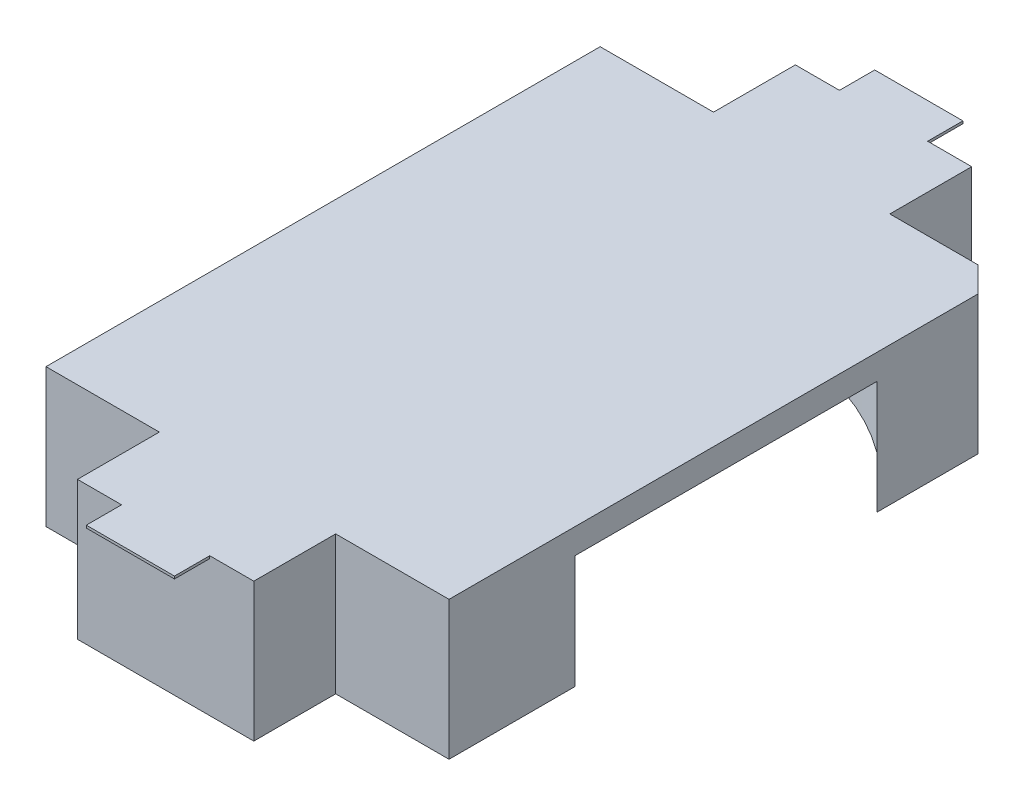
SolidWorks part; units mm, degrees
ref_plane "Front" through (0, 0, 0) normal (0, 0, 1) x (1, 0, 0)
ref_plane "Top" through (0, 0, 0) normal (0, 1, 0) x (1, 0, 0)
ref_plane "Right" through (0, 0, 0) normal (1, 0, 0) x (0, 0, -1)
sketch "Sketch1" plane through (0, 0, 0) normal (0, 1, 0) x (1, 0, 0)
  line L0 (7, 11) -> (8, 10)
  line L1 (-8, -11) -> (8, -11)
  line L2 (-8, -11) -> (-8, 11)
  line L3 (-8, 11) -> (7, 11)
  line L4 (8, -11) -> (8, 10)
  line L5 (-8, -11) -> (8, 11) construction
  line L6 (-8, 11) -> (8, -11) construction
  point P0 (0, 0)
  dimension "D1" = 16
  dimension "D2" = 22
extrude "Boss-Extrude1" add sketch "Sketch1" along normal blind 1
sketch "Sketch2" plane through (0, 0, 0) normal (0, -1, 0) x (1, 0, 0)
  line L0 (-8, -11) -> (-8, -6)
  line L1 (-8, 11) -> (8, 11)
  line L2 (8, 11) -> (8, 6)
  line L3 (8, -10) -> (7, -11)
  line L4 (7, -11) -> (-8, -11)
  line L5 (-8, 6) -> (-8, 11)
  line L6 (8, -6) -> (8, -10)
  arc A0 (-8, -6) -> (8, -6) centre (0, 0) ccw
  arc A1 (8, 6) -> (-8, 6) centre (0, 0) ccw
  dimension "D1" = 20
extrude "Boss-Extrude2" add sketch "Sketch2" along normal blind 4.5
sketch "Sketch3" plane through (0, 1, 0) normal (0, 1, 0) x (1, 0, 0)
  line L0 (-3.5, -11) -> (3.5, -11)
  line L1 (3.5, 14.25) -> (-3.5, 14.25)
  line L2 (3.5, 14.25) -> (3.5, 11)
  line L3 (3.5, -14.25) -> (-3.5, -14.25)
  line L4 (-3.5, 14.25) -> (-3.5, 11)
  line L5 (3.5, 14.25) -> (-3.5, -14.25) construction
  line L6 (3.5, -14.25) -> (-3.5, 14.25) construction
  line L7 (-8, -11) -> (8, -11) construction
  line L8 (-3.5, 11) -> (3.5, 11)
  line L9 (7, 11) -> (-8, 11) construction
  line L10 (3.5, -11) -> (3.5, -14.25)
  line L11 (-3.5, -11) -> (-3.5, -14.25)
  point P0 (0, 0)
  dimension "D1" = 7
  dimension "D2" = 28.5
extrude "Boss-Extrude3" add sketch "Sketch3" against normal up to surface (5.5 mm away) up to face at (0, -4.5, 9.5)
sketch "Sketch4" plane through (0, 1, 0) normal (0, 1, 0) x (1, 0, 0)
  line L1 (1.75, -15.65) -> (-1.75, -15.65)
  line L2 (1.75, -15.65) -> (1.75, 15.65)
  line L3 (1.75, 15.65) -> (-1.75, 15.65)
  line L4 (-1.75, -15.65) -> (-1.75, 15.65)
  line L5 (1.75, -15.65) -> (-1.75, 15.65) construction
  line L6 (1.75, 15.65) -> (-1.75, -15.65) construction
  point P0 (0, 0)
  dimension "D1" = 3.5
  dimension "D2" = 31.3
extrude "Boss-Extrude4" add sketch "Sketch4" against normal blind 0.1
sketch "Sketch5" plane through (0, -4.5, 0) normal (0, -1, 0) x (1, 0, 0)
  line L0 (1.8665, 10.5335) -> (1.8665, 7.6665)
  line L1 (1.8665, 7.6665) -> (0.8722, 7.6665)
  line L2 (0.8722, 7.6665) -> (0.8722, 10.5335)
  line L3 (0.8722, 10.5335) -> (1.8665, 10.5335)
  line L4 (0, 14.25) -> (0, 4.5123) construction
  line L5 (-3.5, 14.25) -> (3.5, 14.25) construction
  line L6 (-0.8722, 10.5335) -> (-1.8665, 10.5335)
  line L7 (-0.8722, 7.6665) -> (-0.8722, 10.5335)
  line L8 (-1.8665, 7.6665) -> (-0.8722, 7.6665)
  line L9 (-1.8665, 10.5335) -> (-1.8665, 7.6665)
extrude "Boss-Extrude6" add sketch "Sketch5" against normal blind 0.1 separate body
